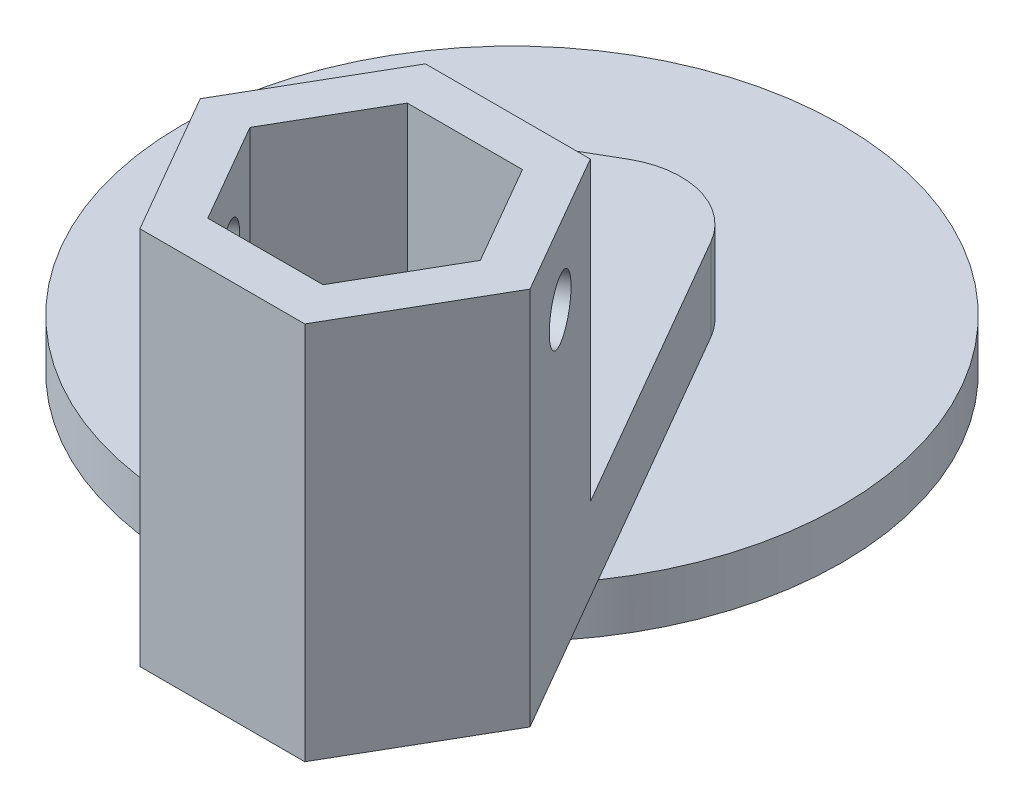
SolidWorks part; units mm, degrees
ref_plane "前视基准面" through (0, 0, 0) normal (0, 0, 1) x (1, 0, 0)
ref_plane "上视基准面" through (0, 0, 0) normal (0, 1, 0) x (1, 0, 0)
ref_plane "右视基准面" through (0, 0, 0) normal (1, 0, 0) x (0, 0, -1)
other "Configuration Table"
sketch "草图1" plane through (0, 0, 0) normal (0, 1, 0) x (1, 0, 0)
  line L1 (6.9859, 0) -> (3.493, 6.05)
  line L2 (3.493, 6.05) -> (-3.493, 6.05)
  line L3 (-3.493, 6.05) -> (-6.9859, 0)
  line L4 (-6.9859, 0) -> (-3.493, -6.05)
  line L5 (-3.493, -6.05) -> (3.493, -6.05)
  line L6 (3.493, -6.05) -> (6.9859, 0)
  line L7 (10, 0) -> (5, 8.6603)
  line L8 (5, 8.6603) -> (-5, 8.6603)
  line L9 (-5, 8.6603) -> (-10, 0)
  line L10 (-10, 0) -> (-5, -8.6603)
  line L11 (-5, -8.6603) -> (5, -8.6603)
  line L12 (5, -8.6603) -> (10, 0)
  circle A0 centre (0, 0) radius 6.05 construction
  circle A1 centre (0, 0) radius 8.6603 construction
  point P1 (5.2395, -3.025)
  dimension "D1" = 6.05
  dimension "D2" = 6.05
  dimension "D3" = 10
  dimension "D4" = 8.6603
extrude "凸台-拉伸3" add sketch "草图1" against normal blind 18
sketch "草图2" plane through (7.5, 0, -4.3301) normal (0.866, 0, -0.5) x (-0.5, 0, -0.866)
  line L2 (-5, -18) -> (-5, 0) construction
  line L3 (-5, 0) -> (5, 0) construction
  circle A0 centre (0, -4.5) radius 1.8
  dimension "D1" = 3.6
  dimension "D2" = 5
  dimension "D3" = 4.5
extrude "切除-拉伸1" cut sketch "草图2" against normal blind 17.325
sketch "草图4" plane through (0, -18, 0) normal (0, -1, 0) x (1, 0, 0)
  line L0 (5, -8.6603) -> (-10, 0)
  line L1 (5, 8.6603) -> (-5, 8.6603)
  line L2 (-5, 8.6603) -> (-10, 0)
  line L3 (-10, 0) -> (-5, -8.6603)
  line L4 (-5, -8.6603) -> (5, -8.6603)
  line L5 (5, -8.6603) -> (10, 0)
  line L6 (10, 0) -> (5, 8.6603)
  circle A0 centre (0, 0) radius 1.75
  circle A2 centre (0, 0) radius 8.6603 construction
  line M2 (-3.493, 6.05) -> (3.493, 6.05)
  line M3 (3.493, 6.05) -> (6.9859, 0)
  line M4 (6.9859, 0) -> (3.493, -6.05)
  line M5 (3.493, -6.05) -> (-3.493, -6.05)
  line M6 (-3.493, -6.05) -> (-6.9859, 0)
  line M7 (-6.9859, 0) -> (-3.493, 6.05)
  line M8 (10, 0) -> (5, 8.6603)
  line M9 (5, 8.6603) -> (-5, 8.6603)
  line M10 (-5, 8.6603) -> (-10, 0)
  line M13 (5, -8.6603) -> (10, 0)
extrude "凸台-拉伸9" add sketch "草图4" along normal blind 5 contours L0 M13 M8 M9 M10 M6 M7 M2 M3 M4 M5 | L0 A0 M5 M4 M3 M2 M7 M6
sketch "草图7" plane through (-2.5, 0, -4.3301) normal (-0.5, 0, -0.866) x (-0.866, 0, 0.5)
  line L1 (8.6603, -18) -> (-8.6603, -18)
  line L2 (8.6603, -18) -> (8.6603, -23)
  line L3 (8.6603, -23) -> (-8.6603, -23)
  line L4 (-8.6603, -18) -> (-8.6603, -23)
extrude "凸台-拉伸10" add sketch "草图7" along normal blind 25
fillet "圆角1" radius 5 1 edges at (-7.5, -20.5, -30.3109)
fillet "圆角2" radius 5 1 edges at (-22.5, -20.5, -21.6506)
sketch "草图8" plane through (0, -23, 0) normal (0, -1, 0) x (1, 0, 0)
  line L4 (-10.6699, -18.4808) -> (-15, -25.9808)
  line L5 (-11.8301, -27.8109) -> (-18.1699, -24.1506) construction
  line L6 (-10.6699, -18.4808) -> (-12.1699, -21.0788)
  circle A2 centre (-12.1699, -21.0788) radius 20
  point P14 (-10.6699, -18.4808)
extrude "凸台-拉伸11" add sketch "草图8" along normal blind 3 contours A2
